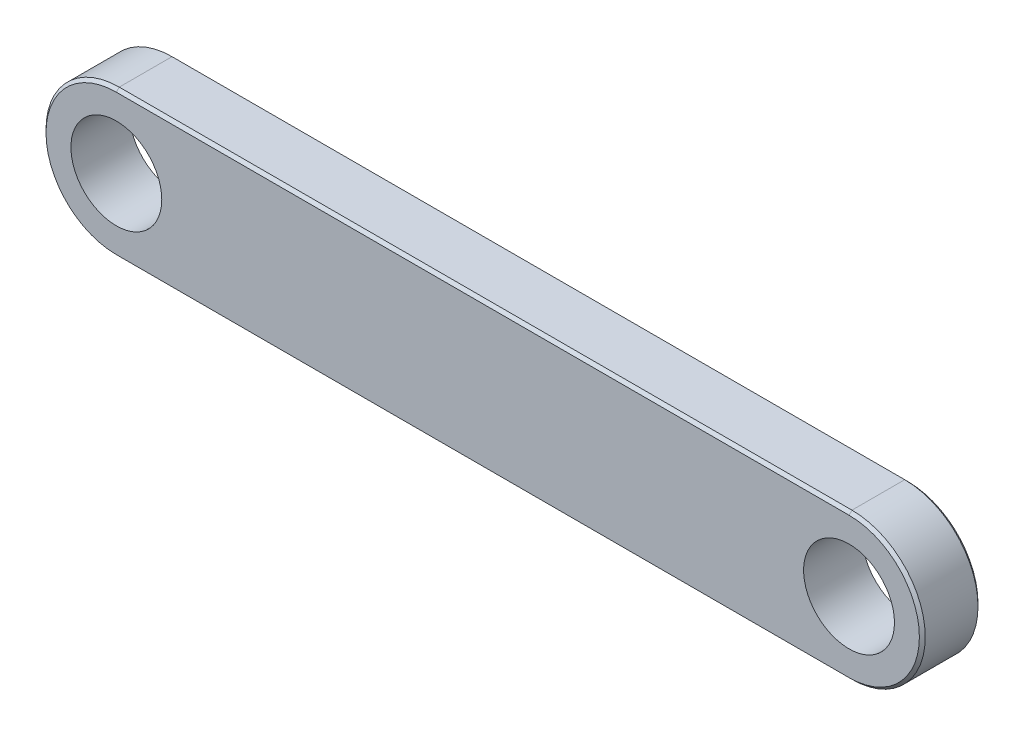
SolidWorks part; units mm, degrees
ref_plane "Front Plane" through (0, 0, 0) normal (0, 0, 1) x (1, 0, 0)
ref_plane "Top Plane" through (0, 0, 0) normal (0, 1, 0) x (1, 0, 0)
ref_plane "Right Plane" through (0, 0, 0) normal (1, 0, 0) x (0, 0, -1)
sketch "Sketch2" plane through (0, 0, 0) normal (0, 0, 1) x (1, 0, 0)
  line L0 (-11.338, 0) -> (13.662, 0) construction
  line L1 (-11.338, 2.5) -> (13.662, 2.5)
  line L2 (-11.338, -2.5) -> (13.662, -2.5)
  arc A0 (-11.338, 2.5) -> (-11.338, -2.5) centre (-11.338, 0) ccw
  arc A1 (13.662, -2.5) -> (13.662, 2.5) centre (13.662, 0) ccw
  circle A2 centre (13.662, 0) radius 1.55
  circle A3 centre (-11.338, 0) radius 1.55
  point P3 (1.162, 0)
  dimension "D2" = 2.5
  dimension "D3" = 3.1
  dimension "D4" = 3.1
  dimension "D1" = 25
extrude "Boss-Extrude1" add sketch "Sketch2" along normal blind 2
chamfer "Chamfer1" distance 0.1 angle 45 8 edges at (1.162, -2.5, 0) (16.162, 0, 0) (-13.838, 0, 0) (1.162, 2.5, 0) (1.162, -2.5, 2) (16.162, 0, 2) (-13.838, 0, 2) (1.162, 2.5, 2)
